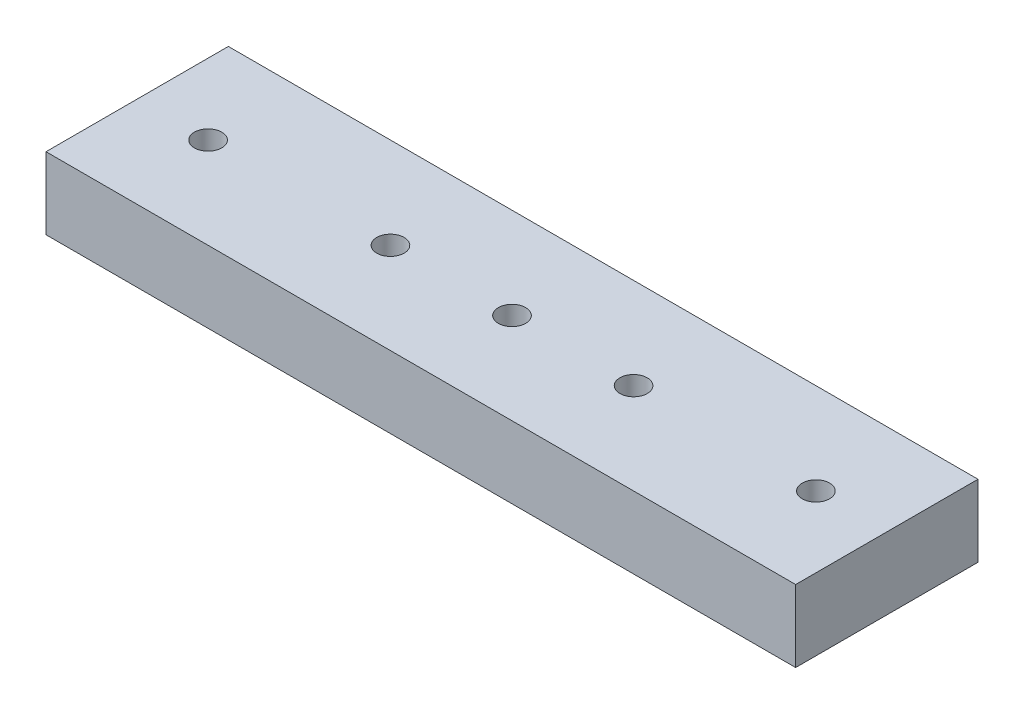
SolidWorks part; units mm, degrees
ref_plane "前视基准面" through (0, 0, 0) normal (0, 0, 1) x (1, 0, 0)
ref_plane "上视基准面" through (0, 0, 0) normal (0, 1, 0) x (1, 0, 0)
ref_plane "右视基准面" through (0, 0, 0) normal (1, 0, 0) x (0, 0, -1)
sketch "草图3" plane through (0, 0, 0) normal (0, 1, 0) x (1, 0, 0)
  line L1 (185, -45) -> (-185, -45)
  line L2 (185, -45) -> (185, 45)
  line L3 (185, 45) -> (-185, 45)
  line L4 (-185, -45) -> (-185, 45)
  line L5 (185, -45) -> (-185, 45) construction
  line L6 (185, 45) -> (-185, -45) construction
  point P0 (0, 0)
  dimension "D1" = 370
  dimension "D2" = 90
extrude "凸台-拉伸2" add sketch "草图3" along normal blind 35.5
hole_wizard "M12 六角头螺栓的柱形沉头孔1" positions "草图5" profile "草图6" counterbore size "M12" standard "GB" end condition through all
sketch "草图5" plane through (0, 0, 0) normal (0, -1, 0) x (-1, 0, 0)
  line L0 (-185, 45) -> (185, 45) construction
  point P0 (-150, 0)
  point P2 (-60, 0)
  point P4 (60, 0)
  point P6 (150, 0)
  point P12 (0, 0)
  point P13 (0, 0)
  dimension "D1" = 60
  dimension "D2" = 60
  dimension "D3" = 90
  dimension "D4" = 90
  dimension "D5" = 45
sketch "草图6" plane through (150, 0, 0) normal (1, 0, 0) x (0, 0, -1)
  line L0 (0, 0) -> (0, 35.5)
  line L1 (0, 35.5) -> (6.75, 35.5)
  line L3 (6.75, 35.5) -> (6.75, 13)
  line L4 (6.75, 13) -> (10, 13)
  line L5 (10, 13) -> (10, 0)
  line L7 (10, 0) -> (0, 0)
  line L11 (0, -6.35) -> (0, 107.95) construction
  dimension "通孔孔直径" = 13.5
  dimension "通孔孔深度" = 35.5
  dimension "柱形沉头孔直径" = 20
  dimension "柱形沉头孔深度" = 13
sketch "草图7" plane through (0, 0, 0) normal (0, -1, 0) x (1, 0, 0)
  line L0 (0, -22.5) -> (0, 22.5) construction
  line L1 (-12.5, -22.5) -> (-12.5, 22.5)
  line L2 (12.5, -22.5) -> (12.5, 22.5)
  arc A0 (-12.5, -22.5) -> (12.5, -22.5) centre (0, -22.5) ccw
  arc A1 (12.5, 22.5) -> (-12.5, 22.5) centre (0, 22.5) ccw
  point P3 (0, 0)
  point P8 (0, 0)
  dimension "D1" = 70
  dimension "D2" = 25
extrude "切除-拉伸1" cut sketch "草图7" against normal blind 13
hole_wizard "M12 六角头螺栓的柱形沉头孔2" positions "草图8" profile "草图9" counterbore size "M12" standard "GB" end condition through all
sketch "草图8" plane through (0, 13, 0) normal (0, -1, 0) x (-1, 0, 0)
  point P0 (0, 0)
sketch "草图9" plane through (0, 13, 0) normal (1, 0, 0) x (0, 0, -1)
  line L0 (0, 0) -> (0, 22.5)
  line L1 (0, 22.5) -> (6.75, 22.5)
  line L3 (6.75, 22.5) -> (6.75, 13)
  line L4 (6.75, 13) -> (10, 13)
  line L5 (10, 13) -> (10, 0)
  line L7 (10, 0) -> (0, 0)
  line L11 (0, -6.35) -> (0, 107.95) construction
  dimension "通孔孔直径" = 13.5
  dimension "通孔孔深度" = 22.5
  dimension "柱形沉头孔直径" = 20
  dimension "柱形沉头孔深度" = 13
